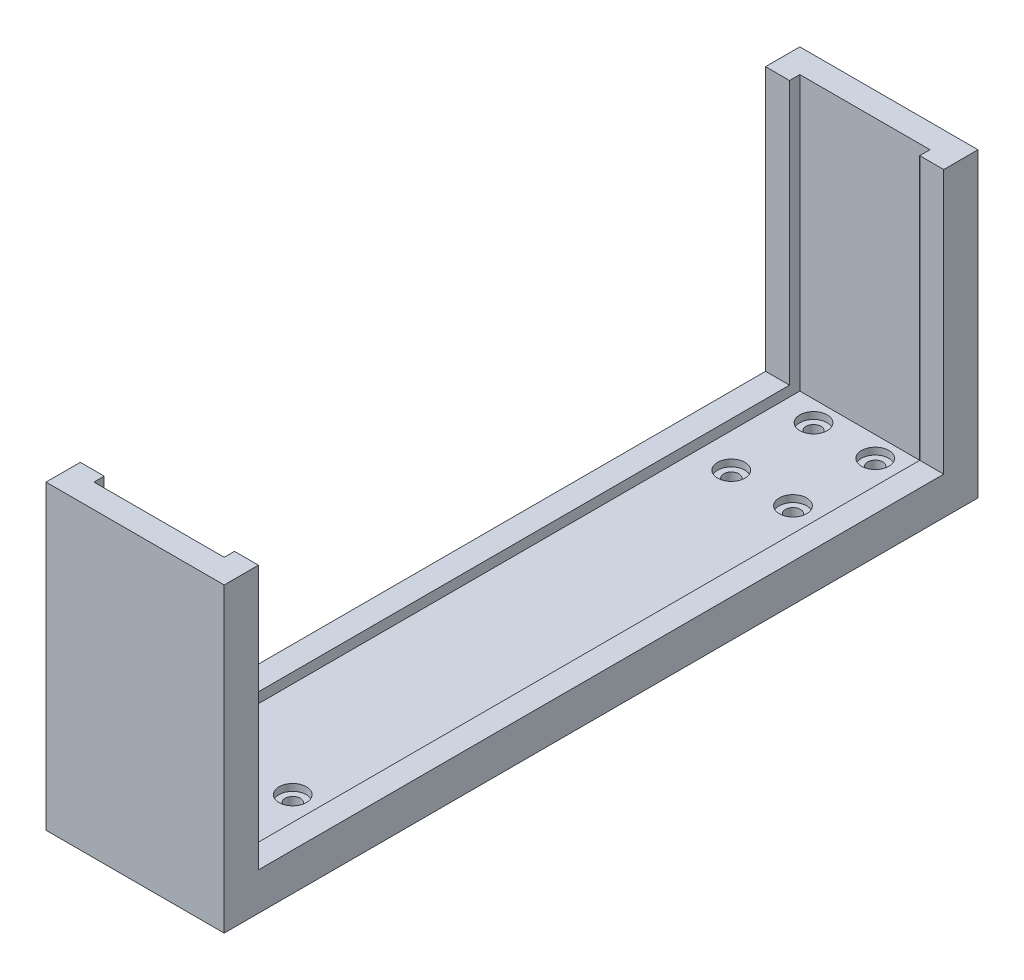
SolidWorks part; units mm, degrees
ref_plane "Front Plane" through (0, 0, 0) normal (0, 0, 1) x (1, 0, 0)
ref_plane "Top Plane" through (0, 0, 0) normal (0, 1, 0) x (1, 0, 0)
ref_plane "Right Plane" through (0, 0, 0) normal (1, 0, 0) x (0, 0, -1)
sketch "Sketch1" plane through (0, 0, 0) normal (0, 1, 0) x (1, 0, 0)
  line L1 (7.7612, 52.9422) -> (59.7612, 52.9422)
  line L2 (7.7612, 52.9422) -> (7.7612, -167.0578)
  line L3 (7.7612, -167.0578) -> (59.7612, -167.0578)
  line L4 (59.7612, 52.9422) -> (59.7612, -167.0578)
  dimension "D1" = 52
  dimension "D2" = 220
extrude "Boss-Extrude1" add sketch "Sketch1" along normal blind 8
sketch "Sketch2" plane through (0, 8, 0) normal (0, 1, 0) x (1, 0, 0)
  line L0 (7.7612, -167.0578) -> (59.7612, -167.0578) construction
  line L1 (7.7612, 52.9422) -> (14.7612, 52.9422)
  line L2 (7.7612, 52.9422) -> (7.7612, -167.0578)
  line L3 (7.7612, -167.0578) -> (14.7612, -167.0578)
  line L4 (14.7612, 52.9422) -> (14.7612, -167.0578)
  dimension "D1" = 7
extrude "Boss-Extrude2" add sketch "Sketch2" along normal blind 80
sketch "Sketch3" plane through (0, 8, 0) normal (0, 1, 0) x (1, 0, 0)
  line L0 (14.7612, -167.0578) -> (14.7612, 52.9422) construction
  line L1 (59.7612, -167.0578) -> (14.7612, -167.0578)
  line L2 (59.7612, -167.0578) -> (59.7612, -160.0578)
  line L3 (59.7612, -160.0578) -> (14.7612, -160.0578)
  line L4 (14.7612, -167.0578) -> (14.7612, -160.0578)
  dimension "D1" = 7
extrude "Boss-Extrude3" add sketch "Sketch3" along normal blind 80
sketch "Sketch4" plane through (0, 8, 0) normal (0, 1, 0) x (1, 0, 0)
  line L0 (14.7612, -160.0578) -> (14.7612, 52.9422) construction
  line L1 (59.7612, 52.9422) -> (14.7612, 52.9422)
  line L2 (59.7612, 52.9422) -> (59.7612, 45.9422)
  line L3 (59.7612, 45.9422) -> (14.7612, 45.9422)
  line L4 (14.7612, 52.9422) -> (14.7612, 45.9422)
  dimension "D1" = 7
extrude "Boss-Extrude4" add sketch "Sketch4" along normal blind 80
sketch "Sketch8" plane through (7.7612, 0, 0) normal (-1, 0, 0) x (0, 0, 1)
  line L0 (-52.9422, 88) -> (167.0578, 88) construction
  line L1 (-42.9422, 88) -> (157.0578, 88)
  line L2 (-42.9422, 88) -> (-42.9422, 8)
  line L3 (-42.9422, 8) -> (157.0578, 8)
  line L4 (157.0578, 88) -> (157.0578, 8)
  line L5 (-52.9422, 0) -> (167.0578, 0) construction
  line L6 (167.0578, 88) -> (167.0578, 0) construction
  line L7 (-52.9422, 88) -> (-52.9422, 0) construction
  dimension "D1" = 0
  dimension "D2" = 8
  dimension "D3" = 10
  dimension "D4" = 10
extrude "Cut-Extrude3" cut sketch "Sketch8" against normal blind 10
sketch "Sketch10" plane through (0, 0, 0) normal (0, -1, 0) x (1, 0, 0)
  circle A0 centre (24.7612, 154.0578) radius 2.2
  circle A1 centre (42.7612, 154.0578) radius 2.2
  circle A2 centre (42.7612, 130.0578) radius 2.2
  circle A3 centre (24.7612, 130.0578) radius 2.2
  circle A4 centre (24.7612, -15.9422) radius 2.2
  circle A5 centre (42.7612, -15.9422) radius 2.2
  circle A6 centre (42.7612, -39.9422) radius 2.2
  circle A7 centre (24.7612, -39.9422) radius 2.2
  dimension "D1" = 4.4
  dimension "D2" = 4.4
  dimension "D3" = 4.4
  dimension "D4" = 4.4
  dimension "D5" = 4.4
  dimension "D6" = 4.4
  dimension "D7" = 4.4
  dimension "D8" = 4.4
extrude "Cut-Extrude5" cut sketch "Sketch10" against normal blind 8
sketch "Sketch11" plane through (0, 8, 0) normal (0, 1, 0) x (1, 0, 0)
  line L0 (59.7612, -160.0578) -> (14.7612, -160.0578) construction
  line L1 (59.7612, 45.9422) -> (52.7612, 45.9422)
  line L2 (59.7612, 45.9422) -> (59.7612, -160.0578)
  line L3 (59.7612, -160.0578) -> (52.7612, -160.0578)
  line L4 (52.7612, 45.9422) -> (52.7612, -160.0578)
  line L6 (14.7612, 42.9422) -> (7.7612, 42.9422)
  line L7 (14.7612, 42.9422) -> (14.7612, -157.0578)
  line L8 (14.7612, -157.0578) -> (7.7612, -157.0578)
  line L9 (7.7612, 42.9422) -> (7.7612, -157.0578)
  dimension "D1" = 7
extrude "Boss-Extrude6" add sketch "Sketch11" along normal blind 3
sketch "Sketch12" plane through (0, 88, 0) normal (0, 1, 0) x (1, 0, 0)
  line L0 (52.7612, 45.9422) -> (52.7612, -160.0578) construction
  line L1 (59.7612, 45.9422) -> (52.7612, 45.9422)
  line L2 (59.7612, 45.9422) -> (59.7612, 42.9422)
  line L3 (59.7612, 42.9422) -> (52.7612, 42.9422)
  line L4 (52.7612, 45.9422) -> (52.7612, 42.9422)
  line L6 (59.7612, -160.0578) -> (52.7612, -160.0578)
  line L7 (59.7612, -160.0578) -> (59.7612, -157.0578)
  line L8 (59.7612, -157.0578) -> (52.7612, -157.0578)
  line L9 (52.7612, -160.0578) -> (52.7612, -157.0578)
  dimension "D1" = 3
  dimension "D2" = 3
extrude "Boss-Extrude7" add sketch "Sketch12" against normal up to surface (77 mm away) up to face at (56.2612, 11, 57.0578)
sketch "Sketch13" plane through (0, 8, 0) normal (0, 1, 0) x (1, 0, 0)
  circle A0 centre (42.7612, -154.0578) radius 4
  circle A1 centre (24.7612, -154.0578) radius 4
  circle A2 centre (24.7612, -130.0578) radius 4
  circle A3 centre (42.7612, -130.0578) radius 4
  circle A4 centre (42.7612, 15.9422) radius 4
  circle A5 centre (24.7612, 15.9422) radius 4
  circle A6 centre (24.7612, 39.9422) radius 4
  circle A7 centre (42.7612, 39.9422) radius 4
  dimension "D1" = 8
  dimension "D2" = 8
  dimension "D3" = 8
  dimension "D4" = 8
  dimension "D5" = 8
  dimension "D6" = 8
  dimension "D7" = 8
  dimension "D8" = 8
extrude "Cut-Extrude6" cut sketch "Sketch13" against normal blind 2
